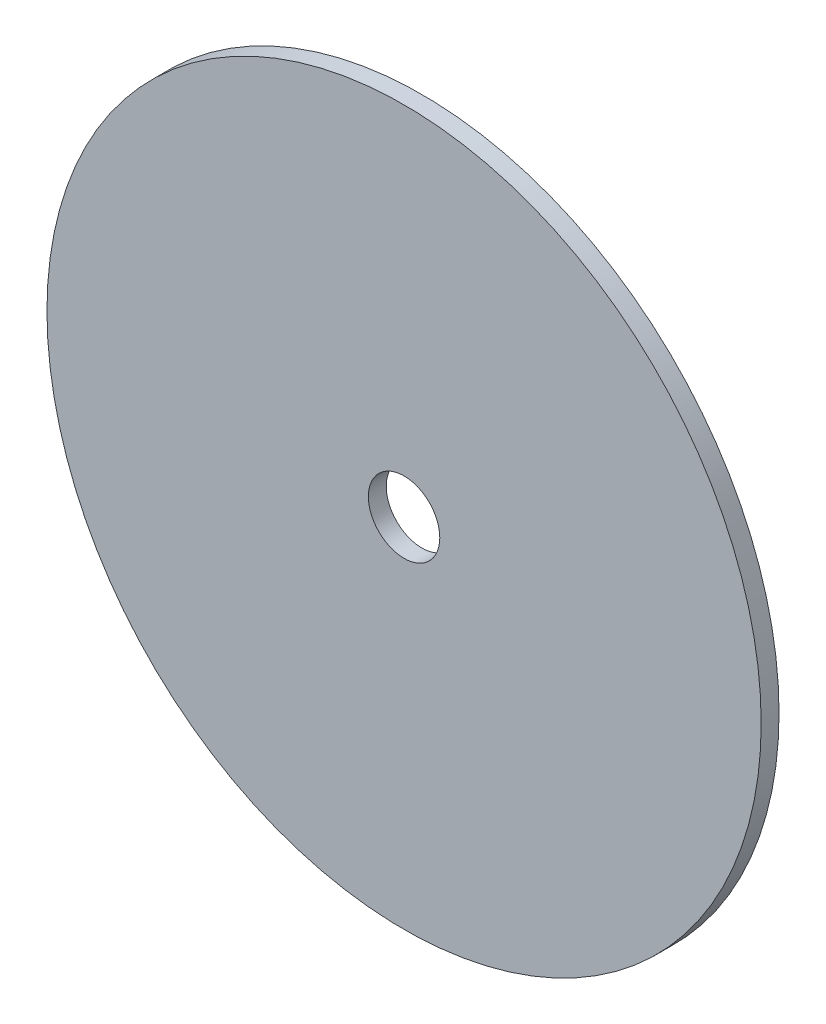
SolidWorks part; units mm, degrees
ref_plane "Front Plane" through (0, 0, 0) normal (0, 0, 1) x (1, 0, 0)
ref_plane "Top Plane" through (0, 0, 0) normal (0, 1, 0) x (1, 0, 0)
ref_plane "Right Plane" through (0, 0, 0) normal (1, 0, 0) x (0, 0, -1)
sketch "Sketch1" plane through (0, 0, 0) normal (0, 0, 1) x (1, 0, 0)
  circle A0 centre (0, 0) radius 20
  circle A1 centre (0, 0) radius 2
  dimension "D1" = 40
  dimension "D2" = 4
extrude "Boss-Extrude1" add sketch "Sketch1" along normal blind 1
